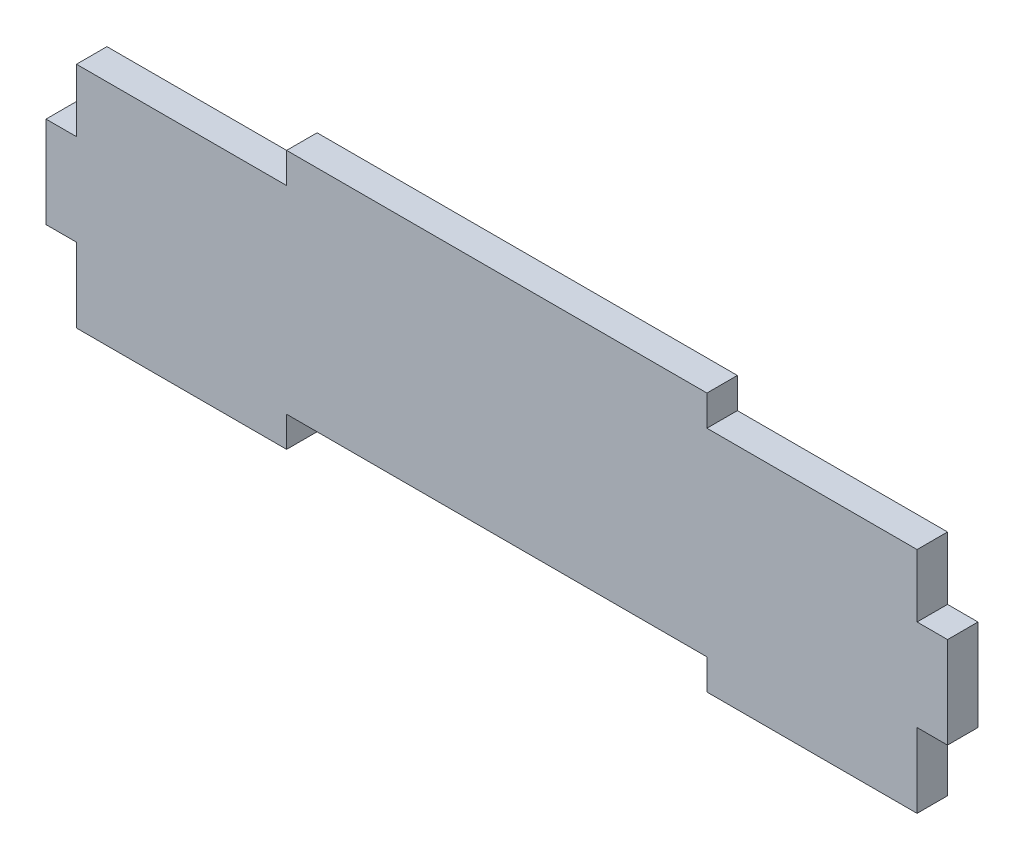
SolidWorks part; units mm, degrees
ref_plane "Front Plane" through (0, 0, 0) normal (0, 0, 1) x (1, 0, 0)
ref_plane "Top Plane" through (0, 0, 0) normal (0, 1, 0) x (1, 0, 0)
ref_plane "Right Plane" through (0, 0, 0) normal (1, 0, 0) x (0, 0, -1)
sketch "Sketch1" plane through (0, 0, 0) normal (0, 0, 1) x (1, 0, 0)
  line L0 (13.7955, 0) -> (27.5909, 0)
  line L1 (27.5909, 0) -> (27.5909, 4.8811)
  line L2 (27.5909, 15) -> (13.7955, 15)
  line L3 (13.7955, 0) -> (13.7955, 2)
  line L4 (13.7955, 2) -> (-13.7955, 2)
  line L5 (13.7955, 15) -> (13.7955, 17)
  line L6 (13.7955, 17) -> (-13.7955, 17)
  line L7 (17.9979, 7.8811) -> (29.5909, 7.8811) construction
  line L8 (29.5909, 4.8811) -> (29.5909, 10.8811)
  line L9 (29.5909, 10.8811) -> (27.5909, 10.8811)
  line L10 (29.5909, 4.8811) -> (27.5909, 4.8811)
  line L11 (27.5909, 10.8811) -> (27.5909, 15)
  line L12 (0, 17) -> (0, 2) construction
  line L13 (-17.9979, 7.8811) -> (-29.5909, 7.8811) construction
  line L14 (-27.5909, 10.8811) -> (-27.5909, 15)
  line L15 (-29.5909, 4.8811) -> (-27.5909, 4.8811)
  line L16 (-29.5909, 10.8811) -> (-27.5909, 10.8811)
  line L17 (-29.5909, 4.8811) -> (-29.5909, 10.8811)
  line L18 (-13.7955, 15) -> (-13.7955, 17)
  line L19 (-13.7955, 0) -> (-13.7955, 2)
  line L20 (-27.5909, 15) -> (-13.7955, 15)
  line L21 (-27.5909, 0) -> (-27.5909, 4.8811)
  line L22 (-13.7955, 0) -> (-27.5909, 0)
  dimension "D1" = 2
  dimension "D2" = 2
  dimension "D3" = 15
  dimension "D4" = 3
  dimension "D5" = 2
extrude "Boss-Extrude4" add sketch "Sketch1" along normal blind 2 contours L20 L18 L6 L5 L2 L11 L9 L8 L10 L1 L0 L3 L4 L19 L22 L21 L15 L17 L16 L14
